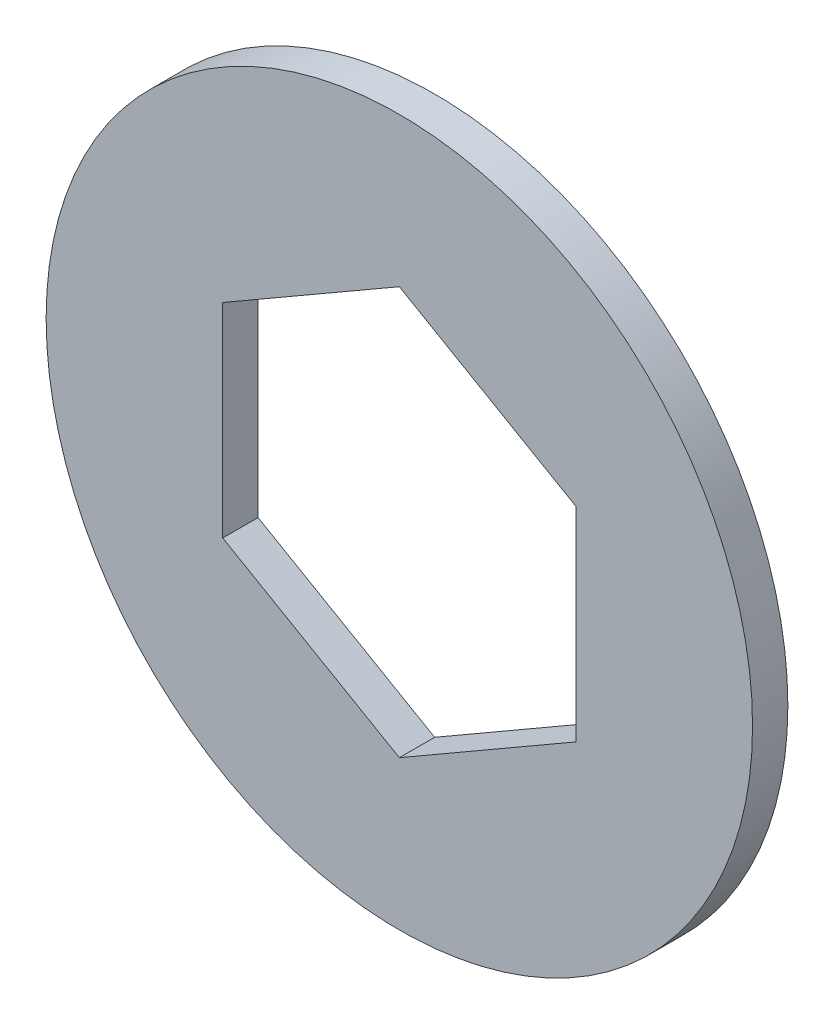
SolidWorks part; units mm, degrees
ref_plane "Front Plane" through (0, 0, 0) normal (0, 0, 1) x (1, 0, 0)
ref_plane "Top Plane" through (0, 0, 0) normal (0, 1, 0) x (1, 0, 0)
ref_plane "Right Plane" through (0, 0, 0) normal (1, 0, 0) x (0, 0, -1)
sketch "Sketch1" plane through (0, 0, 0) normal (0, 0, 1) x (1, 0, 0)
  line L1 (0, 28.8675) -> (-25, 14.4338)
  line L2 (-25, 14.4338) -> (-25, -14.4338)
  line L3 (-25, -14.4338) -> (0, -28.8675)
  line L4 (0, -28.8675) -> (25, -14.4338)
  line L5 (25, -14.4338) -> (25, 14.4338)
  line L6 (25, 14.4338) -> (0, 28.8675)
  circle A0 centre (0, 0) radius 25 construction
  circle A1 centre (0, 0) radius 50
  dimension "D1" = 50
  dimension "D2" = 100
extrude "Boss-Extrude1" add sketch "Sketch1" along normal blind 5
